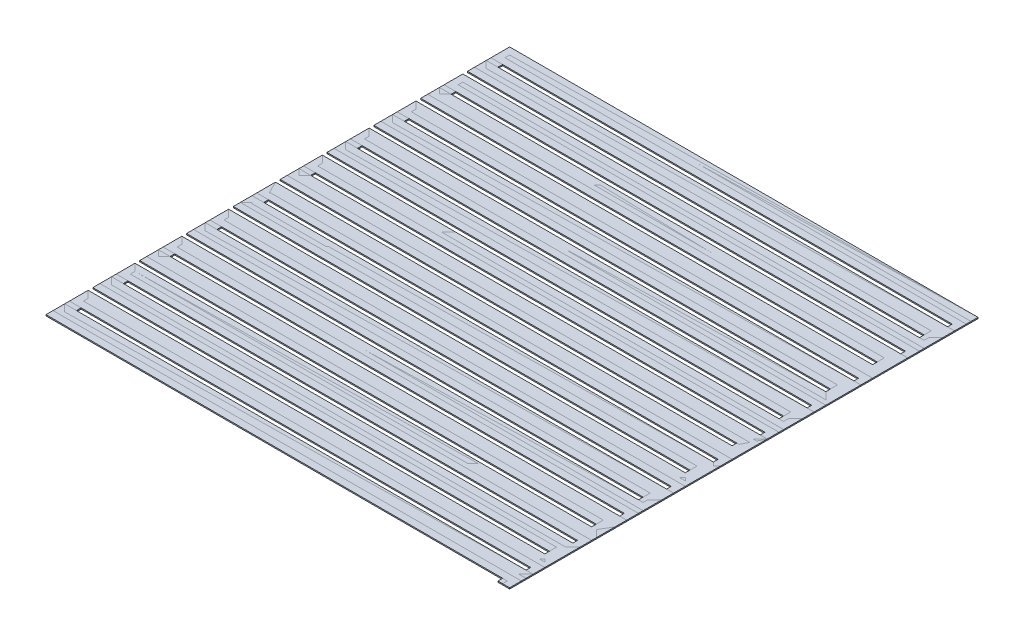
SolidWorks part; units mm, degrees
ref_plane "Front Plane" through (0, 0, 0) normal (0, 0, 1) x (1, 0, 0)
ref_plane "Top Plane" through (0, 0, 0) normal (0, 1, 0) x (1, 0, 0)
ref_plane "Right Plane" through (0, 0, 0) normal (1, 0, 0) x (0, 0, -1)
sketch "Base Guidlines" plane through (0, 0, 0) normal (0, 1, 0) x (1, 0, 0)
  line L0 (-4.5961, 9.2) -> (-4.5961, 8.5)
  line L1 (-10, -10) -> (10, -10)
  line L2 (-10, -10) -> (-10, 10)
  line L3 (-10, 10) -> (10, 10)
  line L4 (10, -10) -> (10, 10)
  line L5 (-10, -10) -> (10, 10) construction
  line L6 (-10, 10) -> (10, -10) construction
  line L7 (-10, 10) -> (10, 10)
  line L8 (-10, 10) -> (-10, 9.2)
  line L9 (-10, 9.2) -> (10, 9.2)
  line L10 (10, 10) -> (10, 9.2)
  line L11 (-4.5961, -9.2) -> (-4.5961, -8.5)
  line L12 (-10, -10) -> (10, -10)
  line L13 (-10, -10) -> (-10, -9.2)
  line L14 (-10, -9.2) -> (10, -9.2)
  line L15 (10, -10) -> (10, -9.2)
  line L17 (-10, -9.2) -> (10, -9.2)
  line L18 (-10, -9.2) -> (-10, -8.5)
  line L19 (-10, -8.5) -> (10, -8.5)
  line L20 (10, -9.2) -> (10, -8.5)
  line L21 (-10, 9.2) -> (10, 9.2)
  line L22 (-10, 9.2) -> (-10, 8.5)
  line L23 (-10, 8.5) -> (10, 8.5)
  line L24 (10, 9.2) -> (10, 8.5)
  point P0 (0, 0)
  dimension "D1" = 20
  dimension "D2" = 20
  dimension "D3" = 0.7
  dimension "D4" = 0.7
sketch "Mirror axis x" plane through (0, 0, 0) normal (0, 1, 0) x (1, 0, 0)
  line L0 (-10, 0) -> (10, 0)
  line L1 (-10, -10) -> (-10, 10) construction
  line L2 (10, -10) -> (10, 10) construction
sketch "TopBlock" plane through (0, 0, 0) normal (0, 1, 0) x (1, 0, 0)
  line L0 (-10, 10) -> (10, -10) construction
  line L1 (-10, 10) -> (-9.7, 10)
  line L2 (-10, 10) -> (-10, 9.7)
  line L3 (10, 9.2) -> (10, 9.5)
  line L4 (-9.7, 10) -> (10, 10)
  line L5 (-9.7, 9.7) -> (-9.7, 9.5)
  line L6 (-10, 9.2) -> (-9.7, 9.2)
  line L7 (-10, 9.2) -> (-10, 9.5)
  line L8 (-9.7, 9.5) -> (9.7, 9.5)
  line L10 (-10, 9.7) -> (-10, 9.5)
  line L11 (-9.7, 9.7) -> (10, 9.7)
  line L12 (10, 9.7) -> (10, 10)
  line L13 (10, -10) -> (10, 10) construction
  line L14 (10, 9.2) -> (9.7, 9.2)
  line L15 (10, 9.5) -> (9.7, 9.5)
  line L24 (9.7, 9.2) -> (-9.7, 9.2)
  dimension "D1" = 0.3
  dimension "D2" = 0.3
extrude "Extruded object" add sketch "TopBlock" along normal blind 0.05
sketch "Mirror axis y" plane through (0, 0, 0) normal (0, 1, 0) x (1, 0, 0)
  line L0 (0, 10) -> (0, -10)
  line L3 (10, 10) -> (-10, 10) construction
  dimension "D1" = 20
sketch "GapandInbetween" plane through (0, 0, 0) normal (0, 1, 0) x (1, 0, 0)
  line L0 (10, 9.2) -> (10, 9)
  line L1 (10, -10) -> (10, 10) construction
  line L2 (10, 9) -> (10, 8.7)
  line L3 (-9.7, 8.5) -> (-9.7, 8.7)
  line L4 (9.7, 9) -> (9.7, 9.2)
  line L5 (-10, 9.2) -> (10, 9.2) construction
  line L6 (9.7, 9.2) -> (10, 9.2)
  line L7 (10, 8.7) -> (-9.7, 8.7)
  line L8 (-10, -10) -> (-10, 10) construction
  line L9 (9.7, 9) -> (-10, 9)
  line L10 (-10, 9) -> (-10, 8.7)
  line L11 (-10, 8.7) -> (-10, 8.5)
  line L12 (-9.7, 8.5) -> (10, 8.5)
  line L13 (-10, 8.5) -> (10, 8.5) construction
  line L14 (-10, 8.5) -> (-10, 8.2)
  line L15 (-10, 8.2) -> (9.7, 8.2)
  line L16 (9.7, 8.2) -> (10, 8.2)
  line L17 (10, 8.2) -> (10, 8.5)
  dimension "D1" = 0.2
  dimension "D2" = 0.3
  dimension "D3" = 0.3
  dimension "D4" = 0.3
  dimension "D5" = 0.3
  dimension "D6" = 19.7
extrude "Boss-Extrude2" add sketch "GapandInbetween" along normal blind 0.05
pattern_linear "LPattern1" count 19 spacing 1 along (0, 0, 1) of "Boss-Extrude2"
sketch "Sketch1" plane through (0, 0, 0) normal (0, 1, 0) x (1, 0, 0)
  line L1 (10, -9.8) -> (10, -10)
  line L2 (9.7, -9.8) -> (9.7, -10)
  line L3 (9.7, -10) -> (10, -10)
  line L4 (10, -9.8) -> (9.7, -9.8)
  line L5 (-10, -9.8) -> (10, -9.8) construction
  dimension "D1" = 0.2
extrude "Boss-Extrude3" add sketch "Sketch1" along normal blind 0.05
sketch "Sketch2" plane through (0, 0, 0) normal (0, 1, 0) x (1, 0, 0)
  line L1 (-10, 10) -> (10, 10)
  line L2 (-10, 10) -> (-10, -10)
  line L3 (-10, -10) -> (10, -10)
  line L4 (10, 10) -> (10, -10)
  dimension "D1" = 20
extrude "Boss-Extrude4" add sketch "Sketch2" along normal blind 0.05 separate body
sketch "Sketch3" plane through (0, 0, 0) normal (0, 1, 0) x (1, 0, 0)
  line L0 (10, -10) -> (10, 10) construction
  line L1 (10, 9.5) -> (-9.5, 9.5)
  line L2 (10, 9.5) -> (10, 9)
  line L3 (10, 9) -> (-9.5, 9)
  line L4 (-9.5, 9.5) -> (-9.5, 9)
  line L5 (10, 10) -> (-10, 10) construction
  line L6 (-10, 10) -> (-10, -10) construction
  dimension "D1" = 0.5
  dimension "D2" = 0.5
  dimension "D3" = 0.5
sketch "Sketch4" plane through (0, 0, 0) normal (0, 1, 0) x (1, 0, 0)
  line L0 (-10, 10) -> (-10, -10) construction
  line L1 (-10, 8.5) -> (9.5, 8.5)
  line L2 (-10, 8.5) -> (-10, 8)
  line L3 (-10, 8) -> (9.5, 8)
  line L4 (9.5, 8.5) -> (9.5, 8)
  line L5 (10, 9) -> (-9.5, 9) construction
  line L6 (10, -10) -> (10, 10) construction
  dimension "D1" = 0.5
  dimension "D2" = 0.5
  dimension "D3" = 0.5
extrude "Cut-Extrude3" cut sketch "Sketch3" along normal blind 0.05
extrude "Cut-Extrude5" cut sketch "Sketch4" along normal blind 0.05
pattern_linear "LPattern2" count 10 spacing 2 along (0, 0, 1) of "Cut-Extrude3"
pattern_linear "LPattern3" count 10 spacing 2 along (0, 0, 1) of "Cut-Extrude5"
sketch "Sketch5" plane through (0, 0, 0) normal (0, -1, 0) x (1, 0, 0)
  line L0 (10, 0) -> (-10, 0) construction
  line L1 (10, -10) -> (-10, -10) construction
  line L2 (10, -10) -> (10, 10) construction
  line L3 (10, 10) -> (-10, 10) construction
  line L4 (-10, -10) -> (-10, 10) construction
  line L5 (0, -10) -> (0, 10) construction
  line L6 (10, -10) -> (0, 0) construction
  line L7 (0, 0) -> (-10, -10) construction
  line L8 (0, 0) -> (-10, 10) construction
  line L9 (0, 0) -> (10, 10) construction
  point P15 (5, -5)
  point P16 (-5, -5)
  point P17 (-5, 5)
  point P18 (5, 5)
sketch "Sketch6" plane through (0, 0, 0) normal (1, 0, 0) x (0, 0, -1)
  line L0 (0, -0.8164) -> (0, 2.1169) construction
